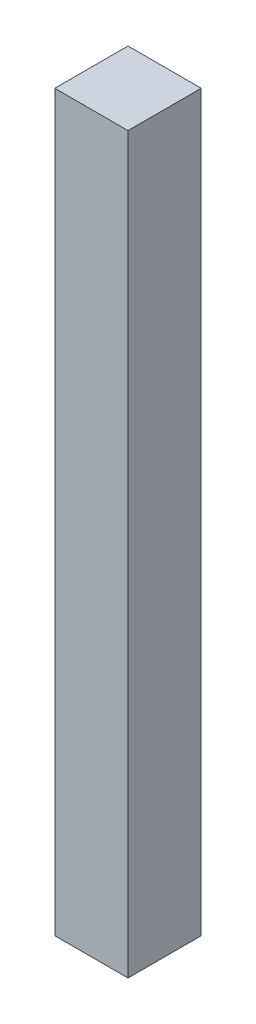
SolidWorks part; units mm, degrees
ref_plane "Front Plane" through (0, 0, 0) normal (0, 0, 1) x (1, 0, 0)
ref_plane "Top Plane" through (0, 0, 0) normal (0, 1, 0) x (1, 0, 0)
ref_plane "Right Plane" through (0, 0, 0) normal (1, 0, 0) x (0, 0, -1)
sketch "Sketch1" plane through (0, 0, 0) normal (0, 0, 1) x (1, 0, 0)
  line L8 (0.0833, -18.9242) -> (0.0833, -48.9842)
  line L19 (0.0833, -48.9842) -> (3.0833, -48.9842)
  line L21 (0.0833, -18.9242) -> (3.0833, -18.9242)
  line L22 (3.0833, -48.9842) -> (3.0833, -18.9242)
  dimension "D1" = 3
extrude "Boss-Extrude2" add sketch "Sketch1" along normal blind 3
